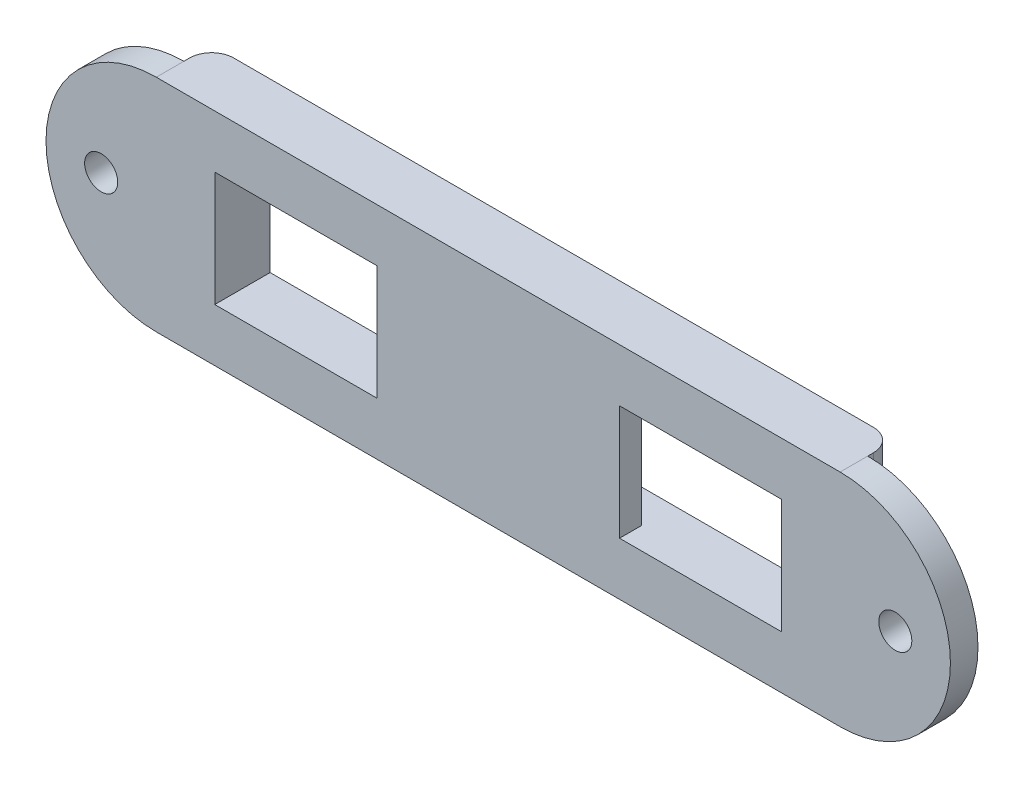
SolidWorks part; units mm, degrees
ref_plane "Front Plane" through (0, 0, 0) normal (0, 0, 1) x (1, 0, 0)
ref_plane "Top Plane" through (0, 0, 0) normal (0, 1, 0) x (1, 0, 0)
ref_plane "Right Plane" through (0, 0, 0) normal (1, 0, 0) x (0, 0, -1)
sketch "Sketch1" plane through (0, 0, 0) normal (0, 0, 1) x (1, 0, 0)
  line L0 (0.1904, 13.035) -> (0.1904, 7.2352)
  line L1 (0.1904, 7.2352) -> (57.296, 7.2352)
  line L2 (57.296, 7.2352) -> (57.296, 13.035)
  line L3 (57.296, 13.035) -> (0.1904, 13.035)
  line L4 (8.7037, 5.7998) -> (8.7037, 0.0019)
  line L5 (47.9637, 5.7998) -> (47.9637, 0.0019)
  line L6 (-3.0363, 38.895) -> (47.9637, 38.895)
  line L7 (47.9637, 38.895) -> (47.9637, 48.895)
  line L8 (47.9637, 48.895) -> (-3.0363, 48.895)
  line L9 (-3.0363, 48.895) -> (-3.0363, 38.895)
  line L10 (-3.0363, 48.895) -> (-3.0363, 49.095)
  line L11 (-3.0363, 48.895) -> (-3.2363, 48.895)
  line L12 (22.4637, 48.895) -> (22.4637, 38.895) construction
  line L13 (-3.0363, 43.895) -> (47.9637, 43.895) construction
  line L14 (47.9637, 48.895) -> (48.1637, 48.895)
  line L15 (47.9637, 48.895) -> (47.9637, 49.095)
  line L16 (-3.0363, 38.895) -> (-3.0363, 38.695)
  line L17 (-3.0363, 38.895) -> (-3.2363, 38.895)
  line L18 (47.9637, 38.895) -> (48.1637, 38.895)
  line L19 (47.9637, 38.895) -> (47.9637, 38.695)
  line L20 (-8.5363, 53.895) -> (53.4637, 53.895)
  line L21 (53.4637, 53.895) -> (53.4637, 33.895)
  line L22 (53.4637, 33.895) -> (-8.5363, 33.895)
  line L23 (-8.5363, 33.895) -> (-8.5363, 53.895)
  line L24 (48.1637, 49.095) -> (48.1637, 38.695)
  line L25 (48.1637, 38.695) -> (-3.2363, 38.695)
  line L26 (-3.2363, 38.695) -> (-3.2363, 49.095)
  line L27 (-3.2363, 49.095) -> (48.1637, 49.095)
  line L28 (22.4637, 53.895) -> (22.4637, 33.895) construction
  line L29 (-8.5363, 43.895) -> (53.4637, 43.895) construction
  dimension "D1" = 62
  dimension "D2" = 20
extrude "Boss-Extrude2" add sketch "Sketch1" along normal blind 3.02 contours L23 L22 L21 L20 L26 L27 L24 L25
sketch "Sketch3" plane through (0, 0, 3.02) normal (0, 0, 1) x (1, 0, 0)
  line L0 (-3.2363, 49.095) -> (-3.2363, 38.695)
  line L1 (-3.2363, 38.695) -> (48.1637, 38.695)
  line L2 (48.1637, 38.695) -> (48.1637, 49.095)
  line L3 (48.1637, 49.095) -> (-3.2363, 49.095)
  line L4 (-8.5363, 53.895) -> (-8.5363, 33.895)
  line L5 (-8.5363, 33.895) -> (53.4637, 33.895)
  line L6 (53.4637, 33.895) -> (53.4637, 53.895)
  line L7 (53.4637, 53.895) -> (-8.5363, 53.895)
extrude "Boss-Extrude3" add sketch "Sketch3" along normal blind 2 contours L7 L4 L5 L6
sketch "Sketch5" plane through (0, 0, 3.02) normal (0, 0, -1) x (-1, 0, 0)
  line L0 (3.2363, 49.095) -> (3.2363, 38.695)
  line L1 (3.2363, 38.695) -> (-48.1637, 38.695)
  line L2 (-48.1637, 38.695) -> (-48.1637, 49.095)
  line L3 (-48.1637, 49.095) -> (3.2363, 49.095)
  line L6 (-39.6637, 49.095) -> (-39.6637, 38.695)
  line L7 (-5.2637, 49.095) -> (-5.2637, 38.695)
  line M6 (-48.1637, 38.695) -> (3.2363, 38.695)
  line M7 (3.2363, 38.695) -> (3.2363, 49.095)
  line M8 (3.2363, 49.095) -> (-48.1637, 49.095)
  line M9 (-48.1637, 49.095) -> (-48.1637, 38.695)
extrude "Cut-Extrude1" cut sketch "Sketch5" against normal blind 10 contours L7 M8 M6 M7 | L6 L3 M9 M6
sketch "Sketch6" plane through (0, 0, 5.02) normal (0, 0, 1) x (1, 0, 0)
  line L0 (5.2637, 49.095) -> (1.0137, 49.095)
  line L1 (5.2637, 49.095) -> (-3.2363, 49.095) construction
  line L2 (1.0137, 49.095) -> (1.0137, 38.695)
  line L3 (-3.2363, 38.695) -> (5.2637, 38.695) construction
  line L4 (1.0137, 38.695) -> (5.2637, 38.695)
  line L5 (5.2637, 38.695) -> (5.2637, 49.095)
  line L6 (39.6637, 49.095) -> (39.6637, 38.695)
  line L7 (39.6637, 38.695) -> (43.9137, 38.695)
  line L8 (39.6637, 38.695) -> (48.1637, 38.695) construction
  line L9 (43.9137, 38.695) -> (43.9137, 49.095)
  line L10 (48.1637, 49.095) -> (39.6637, 49.095) construction
  line L11 (43.9137, 49.095) -> (39.6637, 49.095)
sketch "Sketch19" plane through (0, 0, 5.02) normal (0, 0, 1) x (1, 0, 0)
  line L0 (-6.089, 46.7949) -> (-6.089, 40.9951)
  line L1 (-6.089, 40.9951) -> (51.0165, 40.9951)
  line L2 (51.0165, 40.9951) -> (51.0165, 46.7949)
  line L3 (51.0165, 46.7949) -> (-6.089, 46.7949)
  line L4 (2.6146, 46.7949) -> (2.6146, 40.9971)
  line L5 (41.8747, 46.7949) -> (41.8747, 40.9971)
  line L6 (22.4637, 46.7949) -> (22.4637, 40.9951) construction
  line L7 (-6.089, 43.895) -> (51.0165, 43.895) construction
  line L8 (-3.2363, 43.895) -> (48.1637, 43.895) construction
  line L9 (-3.2363, 49.095) -> (-3.2363, 38.695) construction
  line L10 (48.1637, 38.695) -> (48.1637, 49.095) construction
  line L11 (22.4637, 53.895) -> (22.4637, 33.895) construction
  line L12 (53.4637, 53.895) -> (-8.5363, 53.895) construction
  line L13 (-8.5363, 33.895) -> (53.4637, 33.895) construction
  line L14 (5.2637, 49.095) -> (39.6637, 49.095)
  line L15 (39.6637, 49.095) -> (39.6637, 46.7949)
  line L16 (39.6637, 49.095) -> (39.6637, 38.695) construction
  line L17 (39.6637, 46.7949) -> (5.2637, 46.7949)
  line L18 (5.2637, 38.695) -> (5.2637, 49.095) construction
  line L19 (5.2637, 46.7949) -> (5.2637, 49.095)
  line L20 (5.2637, 38.695) -> (39.6637, 38.695)
  line L21 (39.6637, 38.695) -> (39.6637, 40.9951)
  line L22 (39.6637, 40.9951) -> (5.2637, 40.9951)
  line L23 (5.2637, 40.9951) -> (5.2637, 38.695)
  line M6 (5.2637, 49.095) -> (5.2637, 38.695)
  line M14 (39.6637, 38.695) -> (39.6637, 49.095)
extrude "Cut-Extrude7" cut sketch "Sketch19" against normal blind 4 contours L14 L3 M6 M14 | L20 L1 M6 M14
sketch "Sketch21" plane through (0, 0, 5.02) normal (0, 0, 1) x (1, 0, 0)
  line L0 (22.4637, 53.895) -> (22.4637, 33.895) construction
  line L3 (53.4637, 53.895) -> (-8.5363, 53.895) construction
  line L5 (-8.5363, 33.895) -> (53.4637, 33.895) construction
  line L6 (18.4637, 33.895) -> (26.4637, 33.895)
  line L7 (18.4637, 53.895) -> (26.4637, 53.895)
  line L8 (18.4637, 53.895) -> (18.4637, 33.895)
  line L9 (26.4637, 53.895) -> (26.4637, 33.895)
  line L10 (26.4637, 53.895) -> (33.4637, 53.895)
  line L11 (18.4637, 53.895) -> (11.4637, 53.895)
  line L12 (11.4637, 53.895) -> (11.4637, 33.895)
  line L13 (11.4637, 33.895) -> (18.4637, 33.895)
  line L14 (11.4637, 33.895) -> (18.4637, 33.895)
  line L15 (33.4637, 53.895) -> (33.4637, 33.895)
  line L16 (33.4637, 33.895) -> (26.4637, 33.895)
  line L17 (33.4637, 53.895) -> (26.4637, 53.895)
  line M5 (39.6637, 46.7949) -> (5.2637, 46.7949)
  line M7 (5.2637, 40.9951) -> (39.6637, 40.9951)
extrude "Boss-Extrude11" add sketch "Sketch21" against normal blind 2 contours L15 L10 L9 M5 | L15 L9 M5 M7 | L16 L15 L9 M7 | L12 L13 L8 M7 | L12 L8 M5 M7 | L11 L12 L8 M5 | L7 L0 L9 M5 | L0 L9 M5 M7 | L0 L6 L9 M7 | L0 L8 L6 M7 | L0 L8 M5 M7 | L0 L7 L8 M5
sketch "Sketch22" plane through (0, 0, 5.02) normal (0, 0, 1) x (1, 0, 0)
  line L0 (22.4637, 53.895) -> (22.4637, 33.895) construction
  line L1 (-8.5363, 53.895) -> (53.4637, 53.895) construction
  line L2 (53.4637, 33.895) -> (-8.5363, 33.895) construction
  line L3 (53.4637, 43.895) -> (63.4637, 43.895) construction
  arc A0 (-8.5363, 33.895) -> (-8.5363, 53.895) centre (-8.5363, 43.895) cw
  arc A1 (53.4637, 33.895) -> (53.4637, 53.895) centre (53.4637, 43.895) ccw
  circle A2 centre (58.4637, 43.895) radius 1.5
  circle A3 centre (-13.5363, 43.895) radius 1.5
  line M19 (53.4637, 33.895) -> (53.4637, 53.895)
  line M21 (-8.5363, 53.895) -> (-8.5363, 33.895)
extrude "Boss-Extrude12" add sketch "Sketch22" against normal blind 2.5 contours A1 A2 M19 | A0 A3 M21
fillet "Fillet1" radius 2 1 edges at (53.4637, 43.895, 0)
fillet "Fillet2" radius 2 1 edges at (-8.5363, 43.895, 0)
sketch "Sketch25" plane through (0, 0, 5.02) normal (0, 0, 1) x (1, 0, 0)
  line L0 (-8.5094, 70.788) -> (-8.5094, 64.9882)
  line L1 (-8.5094, 64.9882) -> (48.5962, 64.9882)
  line L2 (48.5962, 64.9882) -> (48.5962, 70.788)
  line L3 (48.5962, 70.788) -> (-8.5094, 70.788)
  line L4 (39.6637, 46.7949) -> (39.6637, 40.9951)
  line L5 (39.6637, 40.9951) -> (5.2637, 40.9951)
  line L6 (5.2637, 40.9951) -> (5.2637, 46.7949)
  line L7 (5.2637, 46.7949) -> (39.6637, 46.7949)
extrude "Boss-Extrude13" add sketch "Sketch25" along normal blind 3.8
sketch "Sketch26" plane through (0, 0, 5.02) normal (0, 0, -1) x (-1, 0, 0)
  line L0 (-48.5962, 70.788) -> (-48.5962, 64.9882)
  line L1 (-48.5962, 64.9882) -> (8.5094, 64.9882)
  line L2 (8.5094, 64.9882) -> (8.5094, 70.788)
  line L3 (8.5094, 70.788) -> (-48.5962, 70.788)
extrude "Cut-Extrude8" cut sketch "Sketch26" against normal blind 3.8
sketch "Sketch27" plane through (0, 40.9951, 0) normal (0, -1, 0) x (1, 0, 0)
  line L0 (5.2637, 5.02) -> (5.2637, 8.82)
  line L1 (5.2637, 5.02) -> (1.0137, 5.02) construction
  line L2 (-8.5363, 5.02) -> (53.4637, 5.02) construction
  line L3 (5.2637, 8.82) -> (39.6637, 8.82)
  line L4 (39.6637, 8.82) -> (39.6637, 5.02)
  line L5 (43.9137, 5.02) -> (39.6637, 5.02) construction
  line L6 (39.6637, 5.02) -> (5.2637, 5.02)
extrude "Cut-Extrude9" cut sketch "Sketch27" against normal blind 20
sketch "Sketch28" plane through (0, 0, 5.02) normal (0, 0, 1) x (1, 0, 0)
  line L0 (33.4637, 46.7949) -> (33.4637, 40.9951)
  line L1 (33.4637, 40.9951) -> (39.6637, 40.9951)
  line L2 (39.6637, 40.9951) -> (39.6637, 46.7949)
  line L3 (39.6637, 46.7949) -> (33.4637, 46.7949)
  line L4 (5.2637, 46.7949) -> (11.4637, 46.7949)
  line L5 (11.4637, 46.7949) -> (11.4637, 40.9951)
  line L6 (11.4637, 40.9951) -> (5.2637, 40.9951)
  line L7 (5.2637, 40.9951) -> (5.2637, 46.7949)
extrude "Cut-Extrude10" cut sketch "Sketch28" against normal blind 20
ref_plane "Plane1" through (-3.2363, 49.095, 0) normal (1, 0, 0) x (0, 0, -1)
